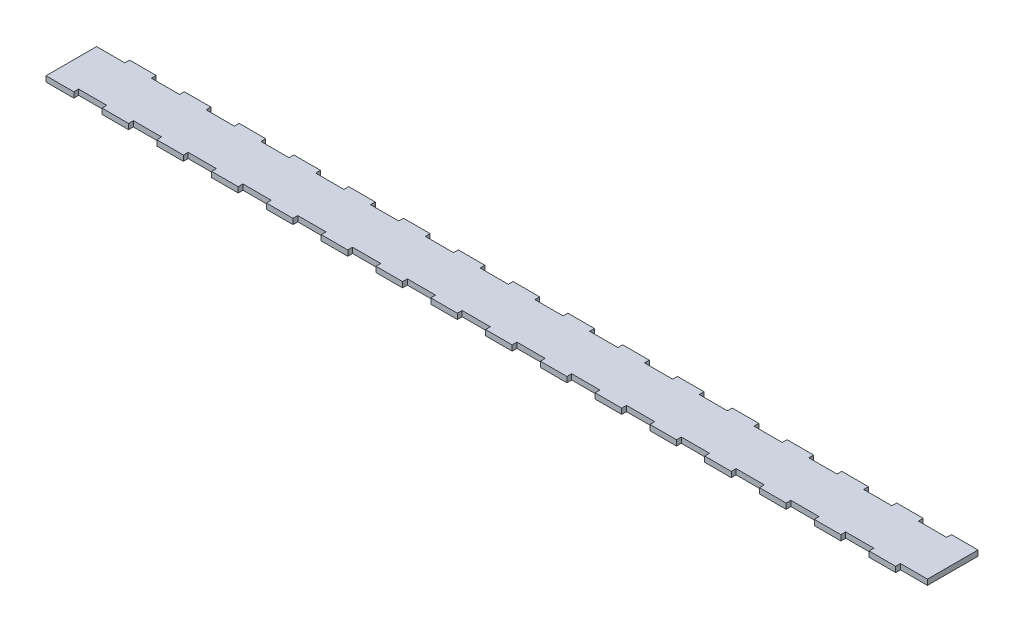
SolidWorks part; units mm, degrees
material "Plain Carbon Steel"
ref_plane "Front Plane" through (0, 0, 0) normal (0, 0, 1) x (1, 0, 0)
ref_plane "Top Plane" through (0, 0, 0) normal (0, 1, 0) x (1, 0, 0)
ref_plane "Right Plane" through (0, 0, 0) normal (1, 0, 0) x (0, 0, -1)
sketch "Sketch1" plane through (0, 0, 0) normal (0, 1, 0) x (1, 0, 0)
  line L1 (320, -20.2) -> (-320, -20.2)
  line L2 (320, -20.2) -> (320, 20.2)
  line L3 (320, 20.2) -> (-320, 20.2)
  line L4 (-320, -20.2) -> (-320, 20.2)
  line L5 (320, -20.2) -> (-320, 20.2) construction
  line L6 (320, 20.2) -> (-320, -20.2) construction
  point P0 (0, 0)
  dimension "D1" = 40.4
  dimension "D2" = 640
extrude "Boss-Extrude1" add sketch "Sketch1" along normal blind 4
sketch "Sketch2" plane through (0, 4, 0) normal (0, 1, 0) x (1, 0, 0)
  line L0 (-320, -20.2) -> (320, -20.2) construction
  line L1 (-299.4, 16.7) -> (-320, 16.7)
  line L2 (-299.4, 16.7) -> (-299.4, 20.2)
  line L3 (-299.4, 20.2) -> (-320, 20.2)
  line L4 (-320, 16.7) -> (-320, 20.2)
  line L5 (-299.4, 16.7) -> (-320, 20.2) construction
  line L6 (-299.4, 20.2) -> (-320, 16.7) construction
  line L7 (-299.7, -16.7) -> (-279.1, -16.7)
  line L8 (-299.7, -16.7) -> (-299.7, -20.2)
  line L9 (-299.7, -20.2) -> (-279.1, -20.2)
  line L10 (-279.1, -16.7) -> (-279.1, -20.2)
  line L11 (-299.7, -16.7) -> (-279.1, -20.2) construction
  line L12 (-299.7, -20.2) -> (-279.1, -16.7) construction
  point P0 (-309.7, 18.45)
  point P6 (-289.4, -18.45)
  dimension "D1" = 3.5
  dimension "D2" = 20.6
  dimension "D3" = 0.3
extrude "Cut-Extrude1" cut sketch "Sketch2" against normal blind 4
pattern_linear "LPattern1" count 17 spacing 40 along (1, 0, 0) of "Cut-Extrude1"
